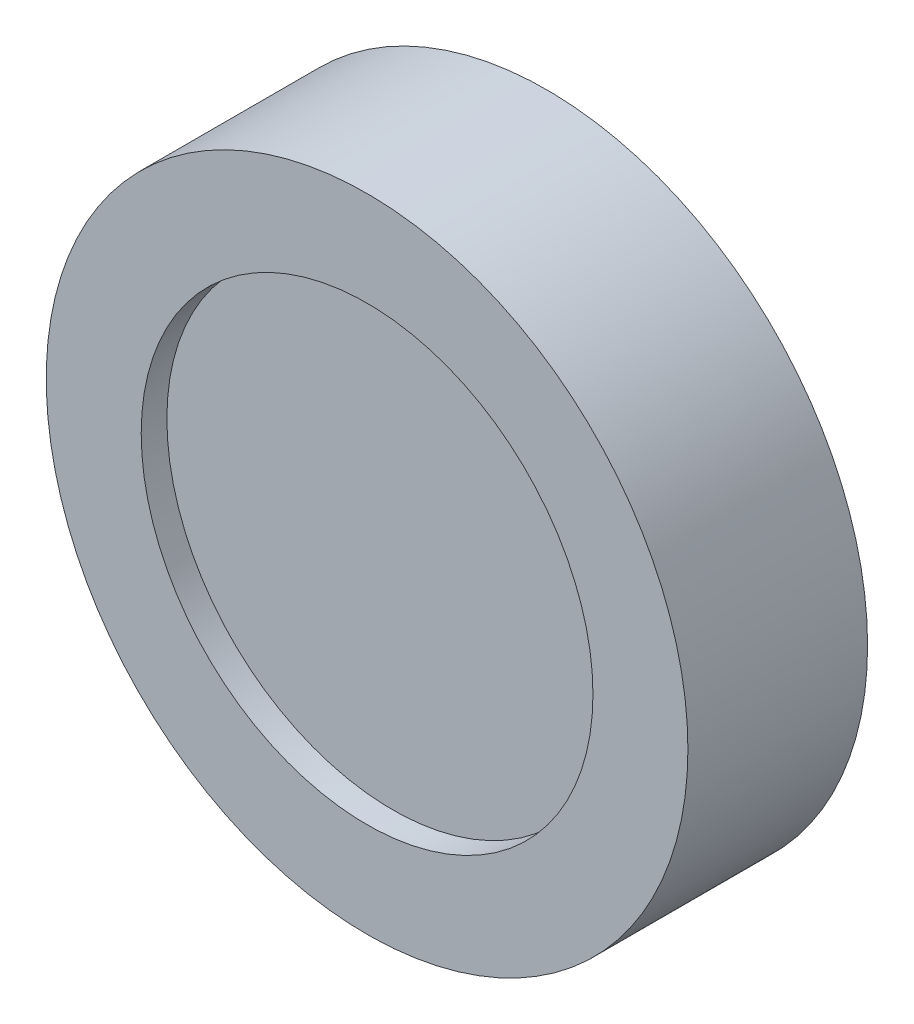
SolidWorks part; units mm, degrees
ref_plane "Front Plane" through (0, 0, 0) normal (0, 0, 1) x (1, 0, 0)
ref_plane "Top Plane" through (0, 0, 0) normal (0, 1, 0) x (1, 0, 0)
ref_plane "Right Plane" through (0, 0, 0) normal (1, 0, 0) x (0, 0, -1)
sketch "Sketch1" plane through (0, 0, 0) normal (0, 0, 1) x (1, 0, 0)
  circle A0 centre (0, 0) radius 6.25
  dimension "D1" = 12.5
extrude "Boss-Extrude1" add sketch "Sketch1" along normal blind 3.5
ref_plane "Plane1" through (0, 0, 1.75) normal (0, 0, 1) x (1, 0, 0)
sketch "Sketch2" plane through (0, 0, 3.5) normal (0, 0, 1) x (1, 0, 0)
  circle A0 centre (0, 0) radius 4.4
  dimension "D1" = 8.8
extrude "Cut-Extrude1" cut sketch "Sketch2" against normal blind 0.5
mirror "Mirror1" about plane through (0, 0, 1.75) normal (0, 0, 1) of "Cut-Extrude1"
